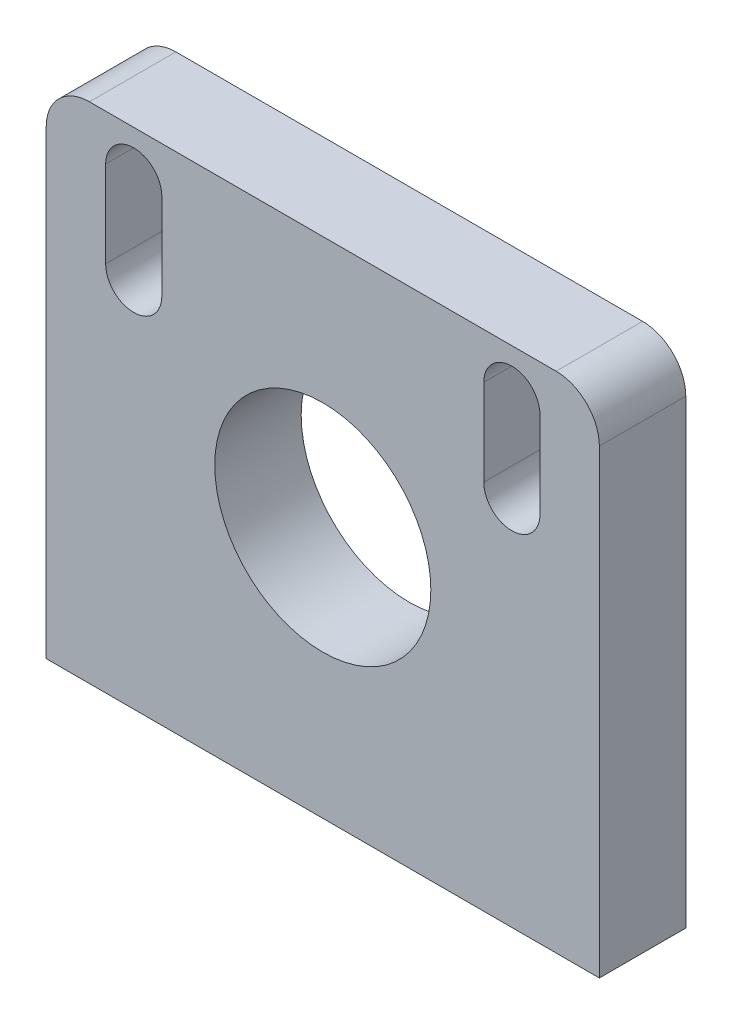
SolidWorks part; units mm, degrees
ref_plane "Front Plane" through (0, 0, 0) normal (0, 0, 1) x (1, 0, 0)
ref_plane "Top Plane" through (0, 0, 0) normal (0, 1, 0) x (1, 0, 0)
ref_plane "Right Plane" through (0, 0, 0) normal (1, 0, 0) x (0, 0, -1)
sketch "Sketch2" plane through (0, 0, 0) normal (0, 0, 1) x (1, 0, 0)
  line L0 (0, 0) -> (0, 29.15) construction
  line L1 (-32, -29.15) -> (32, -29.15)
  line L2 (-32, -29.15) -> (-32, 29.15)
  line L3 (-32, 29.15) -> (32, 29.15)
  line L4 (32, -29.15) -> (32, 29.15)
  line L5 (-32, -29.15) -> (32, 29.15) construction
  line L6 (-32, 29.15) -> (32, -29.15) construction
  line L7 (-21.875, 23.85) -> (-21.875, 13.85) construction
  line L8 (-18.625, 23.85) -> (-18.625, 13.85)
  line L9 (-25.125, 23.85) -> (-25.125, 13.85)
  line L10 (21.875, 23.85) -> (21.875, 13.85) construction
  line L11 (18.625, 23.85) -> (18.625, 13.85)
  line L12 (25.125, 23.85) -> (25.125, 13.85)
  circle A0 centre (-21.875, 23.85) radius 3.25
  circle A2 centre (21.875, 23.85) radius 3.25
  arc A3 (-18.625, 23.85) -> (-25.125, 23.85) centre (-21.875, 23.85) ccw
  arc A4 (-25.125, 13.85) -> (-18.625, 13.85) centre (-21.875, 13.85) ccw
  arc A5 (18.625, 23.85) -> (25.125, 23.85) centre (21.875, 23.85) cw
  arc A6 (25.125, 13.85) -> (18.625, 13.85) centre (21.875, 13.85) cw
  point P0 (0, 0)
  point P12 (-21.875, 18.85)
  point P19 (21.875, 18.85)
  dimension "D5" = 6.5
  dimension "D6" = 6.5
  dimension "D1" = 64
  dimension "D2" = 53
  dimension "D3" = 5.3
  dimension "D4" = 43.75
  dimension "D7" = 10
extrude "Boss-Extrude1" add sketch "Sketch2" along normal mid plane 10 contours L1 L4 L3 L2 A4 L9 A0 L8 L12 A6 L11 A2
sketch "Sketch3" plane through (0, -29.15, 0) normal (0, -1, 0) x (1, 0, 0)
  line L0 (0, 5) -> (0, -5) construction
  line L3 (-32, 0) -> (32, 0) construction
  line L4 (-32, 5) -> (-32, -5) construction
  line L5 (32, 5) -> (32, -5) construction
  line L6 (-32, 5) -> (32, 5) construction
  line L7 (-32, -5) -> (32, -5) construction
  circle A0 centre (-24, 0) radius 2.5
  circle A1 centre (24, 0) radius 2.5
  point P4 (0, 0)
  point P7 (0, 0)
  point P14 (0, 0)
  dimension "D2" = 5
  dimension "D1" = 8
extrude "Cut-Extrude1" cut sketch "Sketch3" against normal blind 10
fillet "Fillet1" radius 5 2 edges at (-32, 29.15, 0) (32, 29.15, 0)
sketch "Sketch4" plane through (0, 0, 5) normal (0, 0, 1) x (1, 0, 0)
  circle A0 centre (0, 0) radius 12.5
  dimension "D1" = 25
extrude "Cut-Extrude2" cut sketch "Sketch4" against normal blind 10
